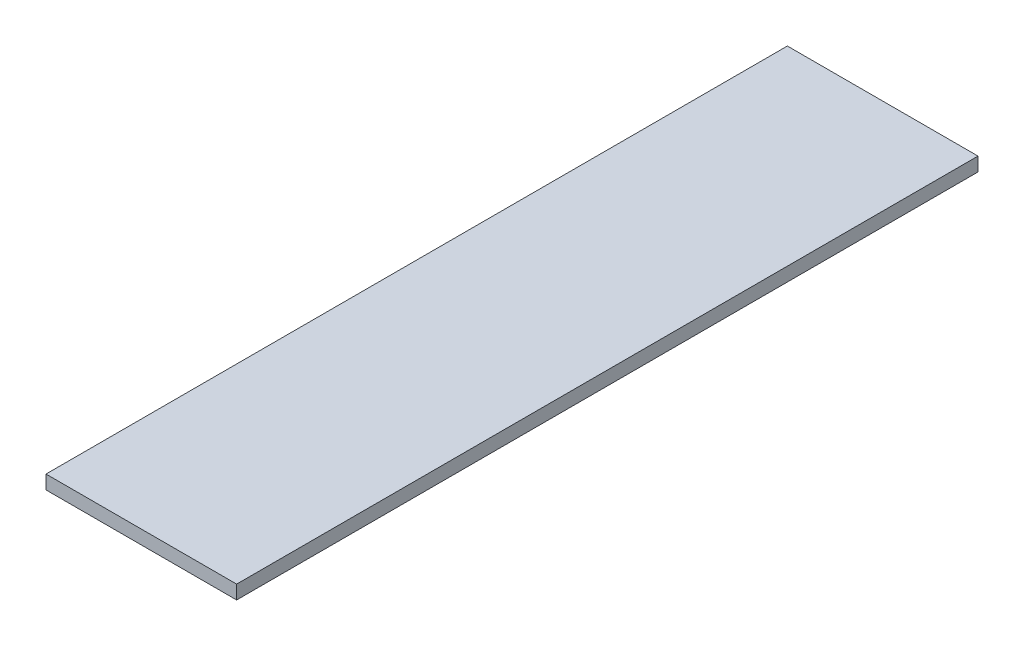
SolidWorks part; units mm, degrees
ref_plane "Front Plane" through (0, 0, 0) normal (0, 0, 1) x (1, 0, 0)
ref_plane "Top Plane" through (0, 0, 0) normal (0, 1, 0) x (1, 0, 0)
ref_plane "Right Plane" through (0, 0, 0) normal (1, 0, 0) x (0, 0, -1)
sketch "Sketch1" plane through (0, 0, 0) normal (0, 0, 1) x (1, 0, 0)
  line L1 (-61.5442, 28.8121) -> (118.4558, 28.8121)
  line L2 (-61.5442, 28.8121) -> (-61.5442, 15.8121)
  line L3 (-61.5442, 15.8121) -> (118.4558, 15.8121)
  line L4 (118.4558, 28.8121) -> (118.4558, 15.8121)
  dimension "D1" = 180
  dimension "D2" = 13
extrude "Boss-Extrude1" add sketch "Sketch1" along normal blind 700
